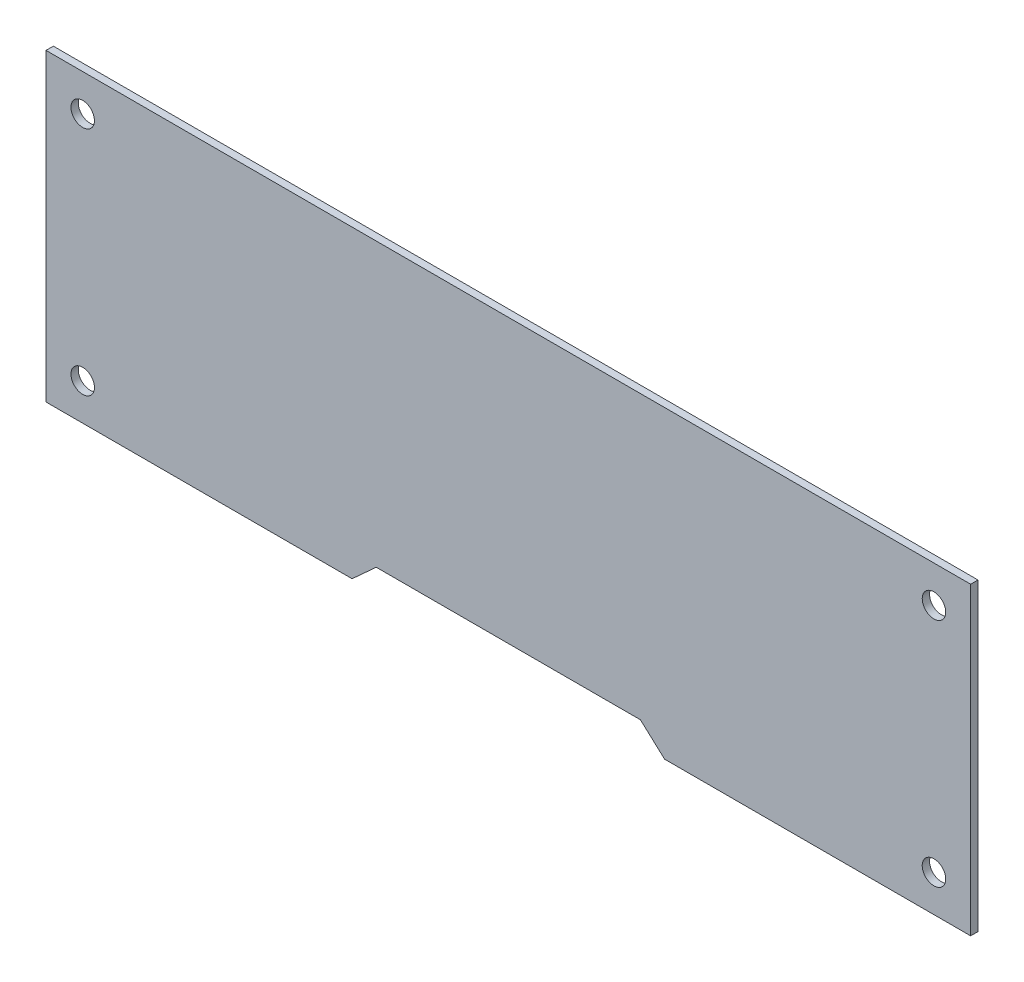
SolidWorks part; units mm, degrees
material "环氧树脂FR-4"
ref_plane "前视基准面" through (0, 0, 0) normal (0, 0, 1) x (1, 0, 0)
ref_plane "上视基准面" through (0, 0, 0) normal (0, 1, 0) x (1, 0, 0)
ref_plane "右视基准面" through (0, 0, 0) normal (1, 0, 0) x (0, 0, -1)
sketch "草图1" plane through (0, 0, 0) normal (0, 0, 1) x (1, 0, 0)
  line L1 (63, -20.75) -> (-63, -20.75)
  line L2 (63, -20.75) -> (63, 20.75)
  line L3 (63, 20.75) -> (-63, 20.75)
  line L4 (-63, -20.75) -> (-63, 20.75)
  line L5 (63, -20.75) -> (-63, 20.75) construction
  line L6 (63, 20.75) -> (-63, -20.75) construction
  point P0 (0, 0)
  dimension "D1" = 126
  dimension "D2" = 41.5
extrude "凸台-拉伸1" add sketch "草图1" along normal blind 1
sketch "草图2" plane through (0, 0, 1) normal (0, 0, 1) x (1, 0, 0)
  line L0 (-63, 0) -> (63, 0) construction
  line L1 (-63, 20.75) -> (-63, -20.75) construction
  line L2 (63, -20.75) -> (63, 20.75) construction
  line L3 (0, -20.75) -> (0, 20.75) construction
  line L4 (-63, -20.75) -> (63, -20.75) construction
  line L5 (63, 20.75) -> (-63, 20.75) construction
  circle A0 centre (-58, 15.75) radius 1.6
  circle A1 centre (-58, -15.75) radius 1.6
  circle A2 centre (58, -15.75) radius 1.6
  circle A3 centre (58, 15.75) radius 1.6
  dimension "D2" = 5
  dimension "D3" = 3.2
  dimension "D1" = 5
extrude "切除-拉伸1" cut sketch "草图2" against normal through all
sketch "草图3" plane through (0, 0, 1) normal (0, 0, 1) x (1, 0, 0)
  line L0 (0, 0) -> (0, -20.75) construction
  line L1 (-63, -20.75) -> (63, -20.75) construction
  line L2 (-21.2922, -20.75) -> (-18, -17.75)
  line L3 (-18, -17.75) -> (18, -17.75)
  line L4 (21.2922, -20.75) -> (18, -17.75)
  line L5 (-21.2922, -20.75) -> (21.2922, -20.75)
  point P9 (0, -17.75)
  dimension "D1" = 3
  dimension "D2" = 18
extrude "切除-拉伸2" cut sketch "草图3" against normal through all
